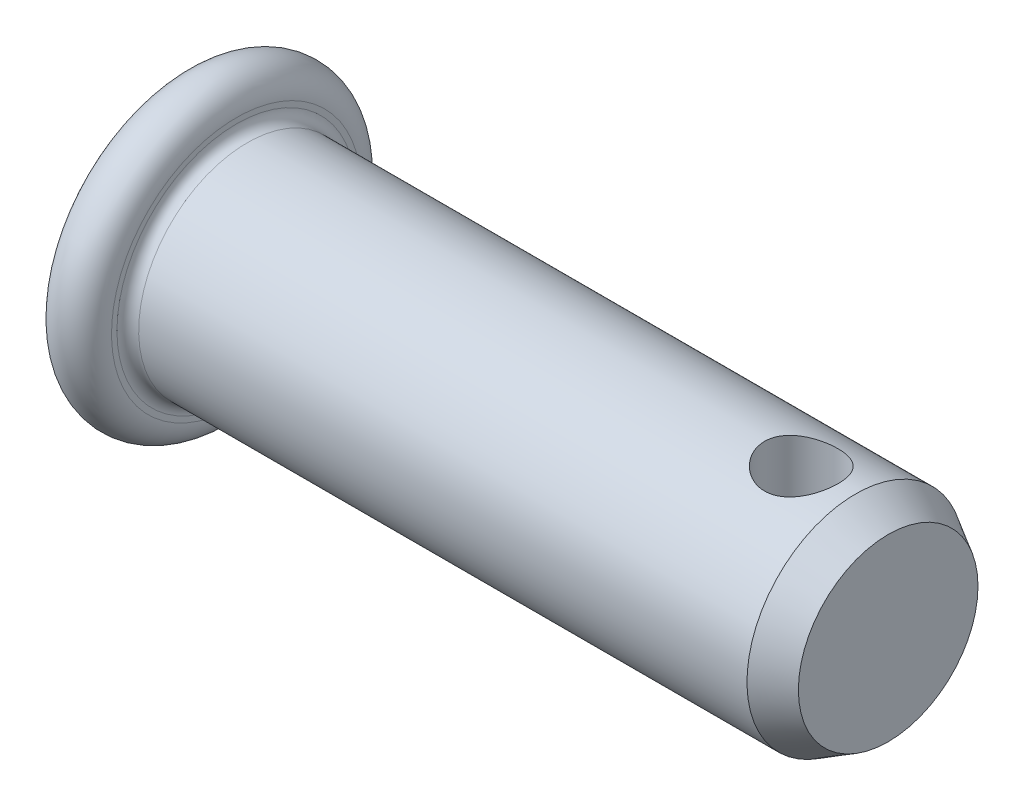
SolidWorks part; units mm, degrees
ref_plane "Front" through (0, 0, 0) normal (0, 0, 1) x (1, 0, 0)
ref_plane "Top" through (0, 0, 0) normal (0, 1, 0) x (1, 0, 0)
ref_plane "Right" through (0, 0, 0) normal (1, 0, 0) x (0, 0, -1)
other "Configuration Table"
sketch "Sketch1" plane through (0, 0, 0) normal (0, 0, 1) x (1, 0, 0)
  line L0 (32.5, 0) -> (0, 0)
  line L1 (0, 0) -> (0, 5.75)
  line L2 (32.5, 0) -> (32.5, 4.134)
  line L3 (32.5, 4.134) -> (31, 5)
  line L4 (31, 5) -> (2.5, 5)
  line L5 (2.5, 5) -> (2.5, 5.75)
  line L6 (-19.83, 0) -> (9.2989, 0) construction
  arc A0 (0, 5.75) -> (2.5, 5.75) centre (1.25, 5.75) cw
  dimension "l" = 30
  dimension "k" = 2.5
  dimension "d" = 10
  dimension "D4" = 30
  dimension "c" = 1.5
  dimension "dk" = 14
revolve "BaseBody" add sketch "Sketch1" angle 360 about L6
fillet "Chamfer1" radius 0.5 1 edges at (2.5, -5, 0)
sketch "Sketch2" plane through (0, 0, 0) normal (0, 1, 0) x (1, 0, 0)
  line L0 (-19.83, 0) -> (9.2989, 0) construction
  line L1 (32.5, -4.134) -> (32.5, 4.134) construction
  circle A0 centre (28.5, 0) radius 1.69
  dimension "D2" = 4
  dimension "d1" = 3.38
extrude "Hole" cut sketch "Sketch2" against normal through all and the other way through all
